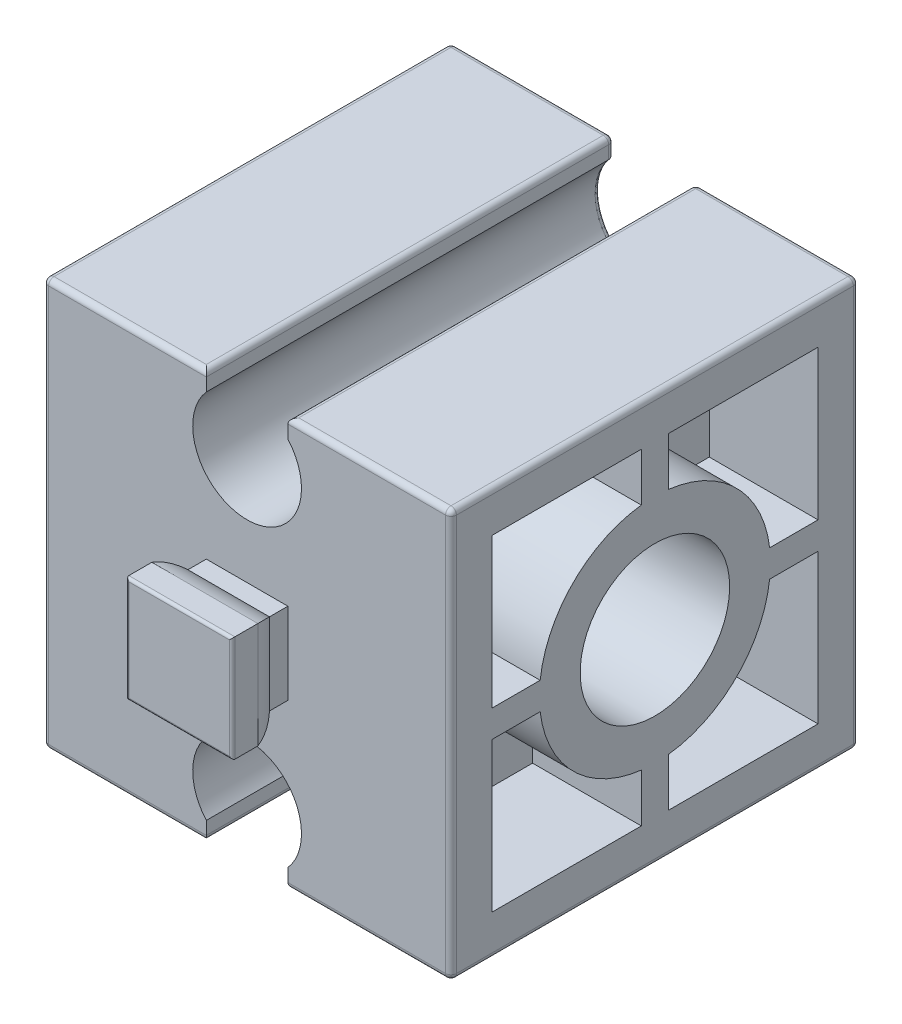
SolidWorks part; units mm, degrees
ref_plane "前视基准面" through (0, 0, 0) normal (0, 0, 1) x (1, 0, 0)
ref_plane "上视基准面" through (0, 0, 0) normal (0, 1, 0) x (1, 0, 0)
ref_plane "右视基准面" through (0, 0, 0) normal (1, 0, 0) x (0, 0, -1)
sketch "草图1" plane through (0, 0, 0) normal (0, 0, 1) x (1, 0, 0)
  line L1 (-7.5, -7.5) -> (7.5, -7.5)
  line L2 (-7.5, -7.5) -> (-7.5, 7.5)
  line L3 (-7.5, 7.5) -> (7.5, 7.5)
  line L4 (7.5, -7.5) -> (7.5, 7.5)
extrude "凸台-拉伸1" add sketch "草图1" against normal blind 15
sketch "草图2" plane through (0, 0, 0) normal (0, 0, 1) x (1, 0, 0)
  line L1 (-1.5, -1.5) -> (1.5, -1.5)
  line L2 (-1.5, -1.5) -> (-1.5, 1.5)
  line L3 (-1.5, 1.5) -> (1.5, 1.5)
  line L4 (1.5, -1.5) -> (1.5, 1.5)
extrude "凸台-拉伸2" add sketch "草图2" along normal blind 1
sketch "草图3" plane through (0, 0, 0) normal (1, 0, 0) x (0, 0, -1)
  line L0 (-2.5, 1.95) -> (-2.5, -1.95)
  line L1 (-2.5, 1.95) -> (-1.5556, 1.95)
  line L2 (-2.5, -1.95) -> (-1.5556, -1.95)
  line L3 (-0.6771, 1.5) -> (-0.6771, -1.5)
  arc A0 (-1.5556, -1.95) -> (-0.6771, -1.5) centre (-2, 0) ccw
  arc A1 (-0.6771, 1.5) -> (-1.5556, 1.95) centre (-2, 0) ccw
extrude "凸台-拉伸3" add sketch "草图3" along normal blind 4 and the other way blind 4 separate body
sketch "草图4" plane through (0, 0, 0) normal (0, 1, 0) x (1, 0, 0)
  line L0 (-4, -2.5) -> (-1.95, -2.5)
  line L1 (-1.95, -2.5) -> (-1.95, -1.5556)
  line L2 (1.95, -2.5) -> (1.95, -1.5556)
  line L3 (-4, -2.5) -> (-4, -0.6771)
  line L4 (-1.5, -0.6771) -> (-4, -0.6771)
  line L5 (4, -0.6771) -> (4, -2.5)
  line L7 (1.95, -2.5) -> (4, -2.5)
  line L8 (-4, -0.6771) -> (4, -0.6771) construction
  line L12 (1.5, -0.6771) -> (4, -0.6771)
  arc A0 (-1.5, -0.6771) -> (-1.95, -1.5556) centre (0, -2) ccw
  arc A1 (1.95, -1.5556) -> (1.5, -0.6771) centre (0, -2) ccw
extrude "切除-拉伸1" cut sketch "草图4" against normal up to next (1.95 mm away) and the other way up to next (1.95 mm away)
sketch "草图5" plane through (-7.5, 0, 0) normal (-1, 0, 0) x (0, 0, 1)
  circle A0 centre (-7.5, 0) radius 2
extrude "切除-拉伸2" cut sketch "草图5" against normal blind 9
sketch "草图6" plane through (-7.5, 0, 0) normal (-1, 0, 0) x (0, 0, 1)
  line L0 (-8, 6.5) -> (-8, 2.958)
  line L1 (-14, -6.5) -> (-8, -6.5)
  line L2 (-14, -6.5) -> (-14, -0.5)
  line L3 (-14, 6.5) -> (-8, 6.5)
  line L4 (-1, -6.5) -> (-1, -0.5)
  line L5 (-7, 6.5) -> (-7, 2.958)
  line L6 (-14, 0.5) -> (-10.458, 0.5)
  line L7 (-14, -0.5) -> (-10.458, -0.5)
  line L8 (-8, -2.958) -> (-8, -6.5)
  line L9 (-4.542, 0.5) -> (-1, 0.5)
  line L10 (-4.542, -0.5) -> (-1, -0.5)
  line L11 (-7, -2.958) -> (-7, -6.5)
  line L12 (-7, 6.5) -> (-1, 6.5)
  line L13 (-14, 0.5) -> (-14, 6.5)
  line L14 (-7, -6.5) -> (-1, -6.5)
  line L15 (-1, 0.5) -> (-1, 6.5)
  arc A0 (-7, -2.958) -> (-4.542, -0.5) centre (-7.5, 0) ccw
  arc A1 (-10.458, -0.5) -> (-8, -2.958) centre (-7.5, 0) ccw
  arc A2 (-8, 2.958) -> (-10.458, 0.5) centre (-7.5, 0) ccw
  arc A3 (-4.542, 0.5) -> (-7, 2.958) centre (-7.5, 0) ccw
extrude "切除-拉伸3" cut sketch "草图6" against normal blind 4
sketch "草图7" plane through (0, 0, 0) normal (0, 0, 1) x (1, 0, 0)
  line L0 (-1.5, -7.5) -> (-1.5, -6.8229)
  line L1 (-7.5, -7.5) -> (7.5, -7.5) construction
  line L2 (1.5, -7.5) -> (1.5, -6.8229)
  line L3 (-1.5, 7.5) -> (1.5, 7.5)
  line L5 (1.5, 7.5) -> (1.5, 6.8229)
  line L6 (-1.5, 7.5) -> (-1.5, 6.8229)
  line L7 (-1.5, -7.5) -> (1.5, -7.5)
  arc A0 (1.5, -6.8229) -> (-1.5, -6.8229) centre (0, -5.5) ccw
  arc A1 (-1.5, 6.8229) -> (1.5, 6.8229) centre (0, 5.5) ccw
extrude "切除-拉伸5" cut sketch "草图7" against normal through all
fillet "圆角1" radius 0.1 4 edges at (1.95, 0, 2.5) (0, -1.95, 2.5) (-1.95, 0, 2.5) (0, 1.95, 2.5)
fillet "圆角2" radius 0.2 26 edges at (0, -3.5, -15) (1.5, -7.1614, -15) (4.5, -7.5, -15) (7.5, 0, -15) (4.5, 7.5, -15) (1.5, 7.1614, -15) (0, 3.5, -15) (-1.5, 7.1614, -15) (-4.5, 7.5, -15) (-7.5, 0, -15) (-4.5, -7.5, -15) (-1.5, -7.1614, -15) (-7.5, 0, 0) (-4.5, 7.5, 0) (4.5, 7.5, 0) (7.5, 0, 0) (4.5, -7.5, 0) (-4.5, -7.5, 0) (7.5, 7.5, -7.5) (1.5, 7.5, -7.5) (-7.5, 7.5, -7.5) (-1.5, 7.5, -7.5) (7.5, -7.5, -7.5) (1.5, -7.5, -7.5) (-7.5, -7.5, -7.5) (-1.5, -7.5, -7.5)
ref_plane "基准面1" through (0, 0, -7.5) normal (0, 0, 1) x (1, 0, 0)
mirror "镜向2" about plane through (0, 0, -7.5) normal (0, 0, 1) of "凸台-拉伸3", "切除-拉伸1", "圆角1", "凸台-拉伸2"
sketch "草图8" plane through (7.5, 0, 0) normal (1, 0, 0) x (0, 0, -1)
  line L0 (0, 0) -> (7.5, 0) construction
  line L1 (13.5, 6) -> (13.5, 0.5)
  line L2 (13.5, 6) -> (8, 6)
  line L3 (13.5, -6) -> (8, -6)
  line L4 (1.5, 6) -> (1.5, 0.5)
  line L5 (13.5, 6) -> (1.5, -6) construction
  line L6 (13.5, -6) -> (1.5, 6) construction
  line L7 (7.5, 0) -> (7.5, 6) construction
  line L8 (11.7205, 0.5) -> (13.5, 0.5)
  line L9 (11.7205, -0.5) -> (13.5, -0.5)
  line L10 (7, 4.2205) -> (7, 6)
  line L11 (8, 4.2205) -> (8, 6)
  line L12 (8, -4.2205) -> (8, -6)
  line L13 (7, -4.2205) -> (7, -6)
  line L14 (3.2795, -0.5) -> (1.5, -0.5)
  line L15 (3.2795, 0.5) -> (1.5, 0.5)
  line L16 (13.5, -0.5) -> (13.5, -6)
  line L17 (7, -6) -> (1.5, -6)
  line L18 (1.5, -0.5) -> (1.5, -6)
  line L19 (7, 6) -> (1.5, 6)
  arc A0 (7, 4.2205) -> (3.2795, 0.5) centre (7.5, 0) ccw
  arc A1 (3.2795, -0.5) -> (7, -4.2205) centre (7.5, 0) ccw
  arc A2 (8, -4.2205) -> (11.7205, -0.5) centre (7.5, 0) ccw
  arc A3 (11.7205, 0.5) -> (8, 4.2205) centre (7.5, 0) ccw
  point P4 (8, 0)
  point P11 (7, 0)
  point P29 (7.5, 0)
  dimension "D2" = 8.5
  dimension "D1" = 7.5
  dimension "D3" = 12
extrude "切除-拉伸6" cut sketch "草图8" against normal blind 4
sketch "草图9" plane through (7.5, 0, 0) normal (1, 0, 0) x (0, 0, -1)
  circle A0 centre (7.5, 0) radius 2.75
  dimension "D1" = 5.5
extrude "切除-拉伸7" cut sketch "草图9" against normal blind 6
